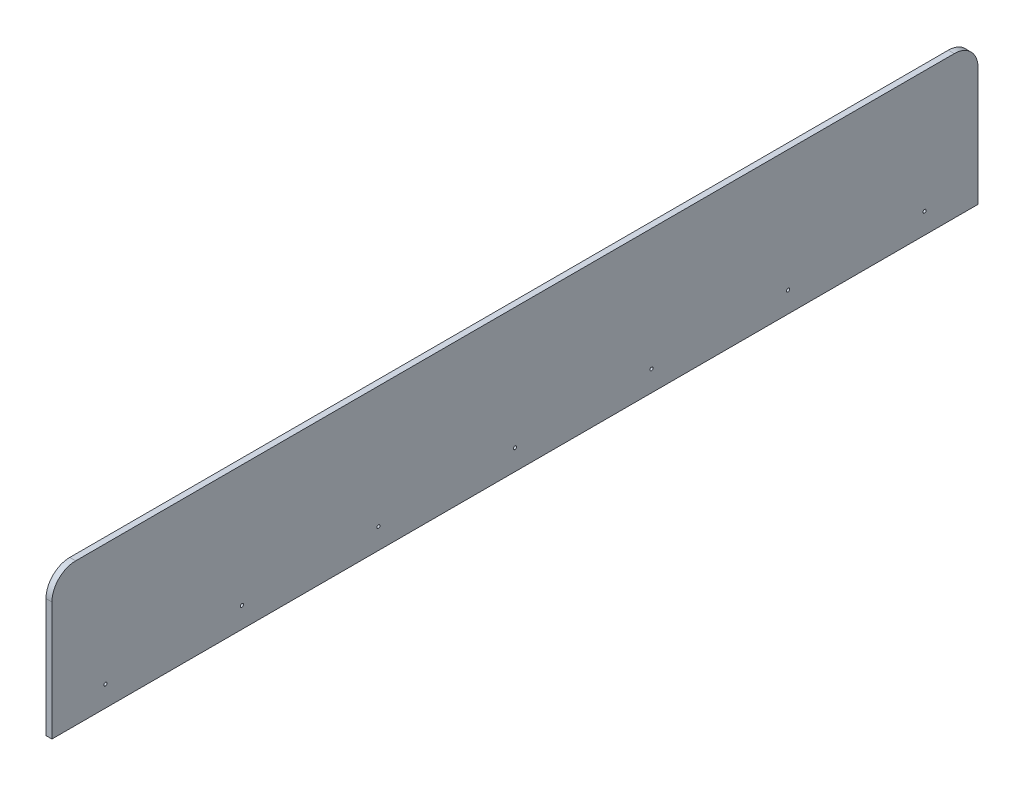
SolidWorks part; units mm, degrees
material "Acrylic (Medium-high impact)"
ref_plane "Front Plane" through (0, 0, 0) normal (0, 0, 1) x (1, 0, 0)
ref_plane "Top Plane" through (0, 0, 0) normal (0, 1, 0) x (1, 0, 0)
ref_plane "Right Plane" through (0, 0, 0) normal (1, 0, 0) x (0, 0, -1)
sketch "Sketch1" plane through (0, 0, 0) normal (1, 0, 0) x (0, 0, -1)
  line L1 (-990.6, -152.4) -> (990.6, -152.4)
  line L2 (-990.6, -152.4) -> (-990.6, 101.6)
  line L3 (-939.8, 152.4) -> (939.8, 152.4)
  line L4 (990.6, -152.4) -> (990.6, 101.6)
  line L5 (-990.6, -152.4) -> (990.6, 152.4) construction
  line L6 (-990.6, 152.4) -> (990.6, -152.4) construction
  line L12 (-406.4, -152.4) -> (1574.8, -152.4) [skipped]
  line L13 (-698.5, -152.4) -> (1282.7, -152.4) [skipped]
  line L14 (-114.3, -152.4) -> (1866.9, -152.4) [skipped]
  line L15 (177.8, -152.4) -> (2159, -152.4) [skipped]
  line L16 (469.9, -152.4) -> (2451.1, -152.4) [skipped]
  line L17 (762, -152.4) -> (2743.2, -152.4) [skipped]
  circle A2 centre (-876.3, -107.95) radius 3.3734
  circle A3 centre (-584.2, -107.95) radius 3.3734
  circle A4 centre (-292.1, -107.95) radius 3.3734
  circle A5 centre (0, -107.95) radius 3.3734
  circle A6 centre (292.1, -107.95) radius 3.3734
  circle A7 centre (584.2, -107.95) radius 3.3734
  circle A8 centre (876.3, -107.95) radius 3.3734
  arc A9 (939.8, 152.4) -> (990.6, 101.6) centre (939.8, 101.6) cw
  arc A10 (-939.8, 152.4) -> (-990.6, 101.6) centre (-939.8, 101.6) ccw
  point P0 (0, 0)
  point P14 (-990.6, 152.4)
  point P15 (990.6, 152.4)
  dimension "D3" = 50.8
  dimension "D4" = 6.7469
  dimension "D1" = 1981.2
  dimension "D2" = 304.8
  dimension "D5" = 44.45
  dimension "D6" = 114.3
  dimension "D8" = 292.1
  dimension "D7" = 7
extrude "Boss-Extrude1" add sketch "Sketch1" along normal blind 12.7
